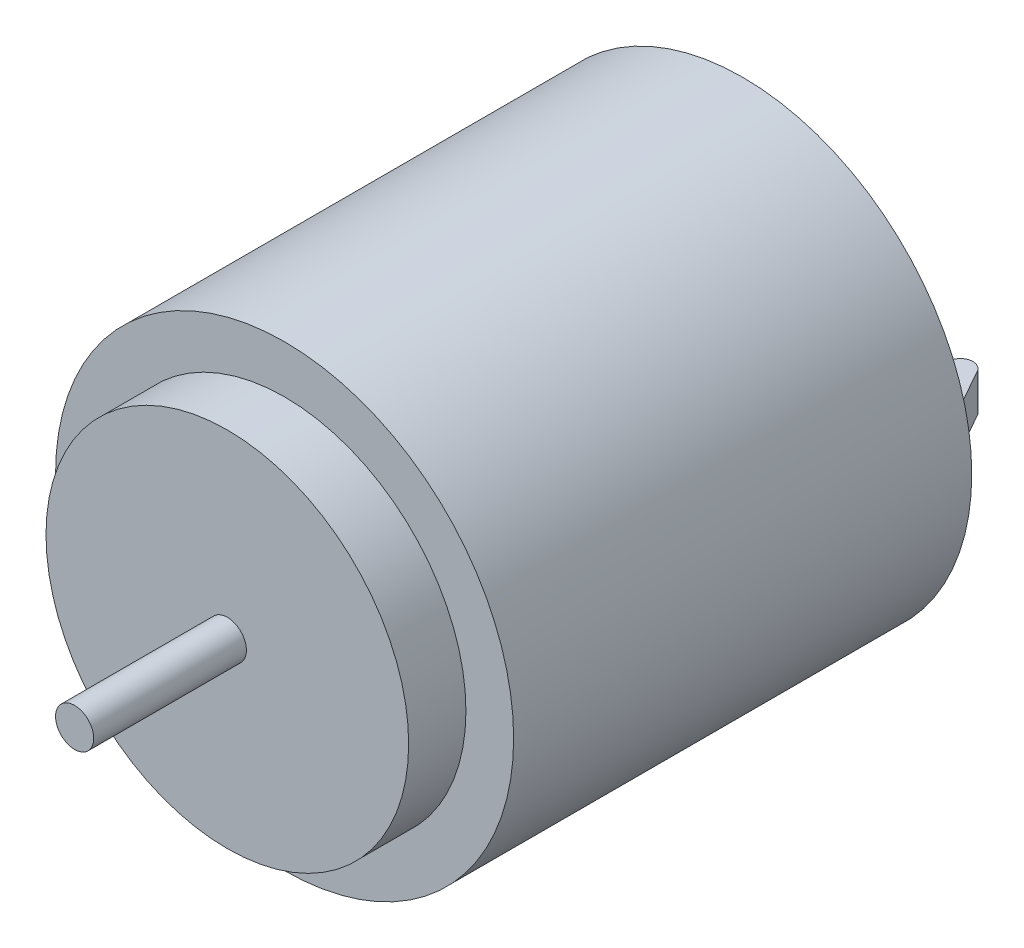
SolidWorks part; units mm, degrees
ref_plane "Front Plane" through (0, 0, 0) normal (0, 0, 1) x (1, 0, 0)
ref_plane "Top Plane" through (0, 0, 0) normal (0, 1, 0) x (1, 0, 0)
ref_plane "Right Plane" through (0, 0, 0) normal (1, 0, 0) x (0, 0, -1)
sketch "Sketch1" plane through (0, 0, 0) normal (0, 1, 0) x (1, 0, 0)
  line L0 (0, 19.7791) -> (0, -21.9436) construction
  line L1 (0, 15.6068) -> (12, 15.6068)
  line L2 (12, 15.6068) -> (12, -8.3932)
  line L3 (12, -8.3932) -> (9.5, -8.3932)
  line L4 (9.5, -8.3932) -> (9.5, -11.3932)
  line L5 (9.5, -11.3932) -> (1, -11.3932)
  line L6 (1, -11.3932) -> (1, -19.3932)
  line L7 (1, -19.3932) -> (0, -19.3932)
  line L8 (0, -19.3932) -> (0, 15.6068)
  dimension "D1" = 12
  dimension "D2" = 24
  dimension "D3" = 3
  dimension "D4" = 9.5
  dimension "D5" = 8
  dimension "D6" = 1
revolve "Revolve1" add sketch "Sketch1" angle 360 about L8
sketch "Sketch3" plane through (0, 0, 0) normal (0, 1, 0) x (1, 0, 0)
  line L0 (9.858, 15.6068) -> (7.9244, 19.0905) construction
  line L1 (12, 15.6068) -> (-12, 15.6068) construction
  line L2 (9.2895, 15.2913) -> (7.3558, 18.7749)
  line L3 (10.4266, 15.9224) -> (8.4929, 19.4061)
  line L4 (0, 24.0984) -> (0, 9.4201) construction
  line L5 (-9.858, 15.6068) -> (-7.9244, 19.0905) construction
  line L6 (-9.2895, 15.2913) -> (-7.3558, 18.7749)
  line L7 (-10.4266, 15.9224) -> (-8.4929, 19.4061)
  arc A0 (9.2895, 15.2913) -> (10.4266, 15.9224) centre (9.858, 15.6068) ccw
  arc A1 (8.4929, 19.4061) -> (7.3558, 18.7749) centre (7.9244, 19.0905) ccw
  arc A2 (-9.2895, 15.2913) -> (-10.4266, 15.9224) centre (-9.858, 15.6068) cw
  arc A3 (-8.4929, 19.4061) -> (-7.3558, 18.7749) centre (-7.9244, 19.0905) cw
  point P4 (8.8912, 17.3487)
  point P14 (-8.8912, 17.3487)
  dimension "D1" = 1.3005
  dimension "D2" = 3.9843
extrude "Boss-Extrude1" add sketch "Sketch3" along normal mid plane 2
